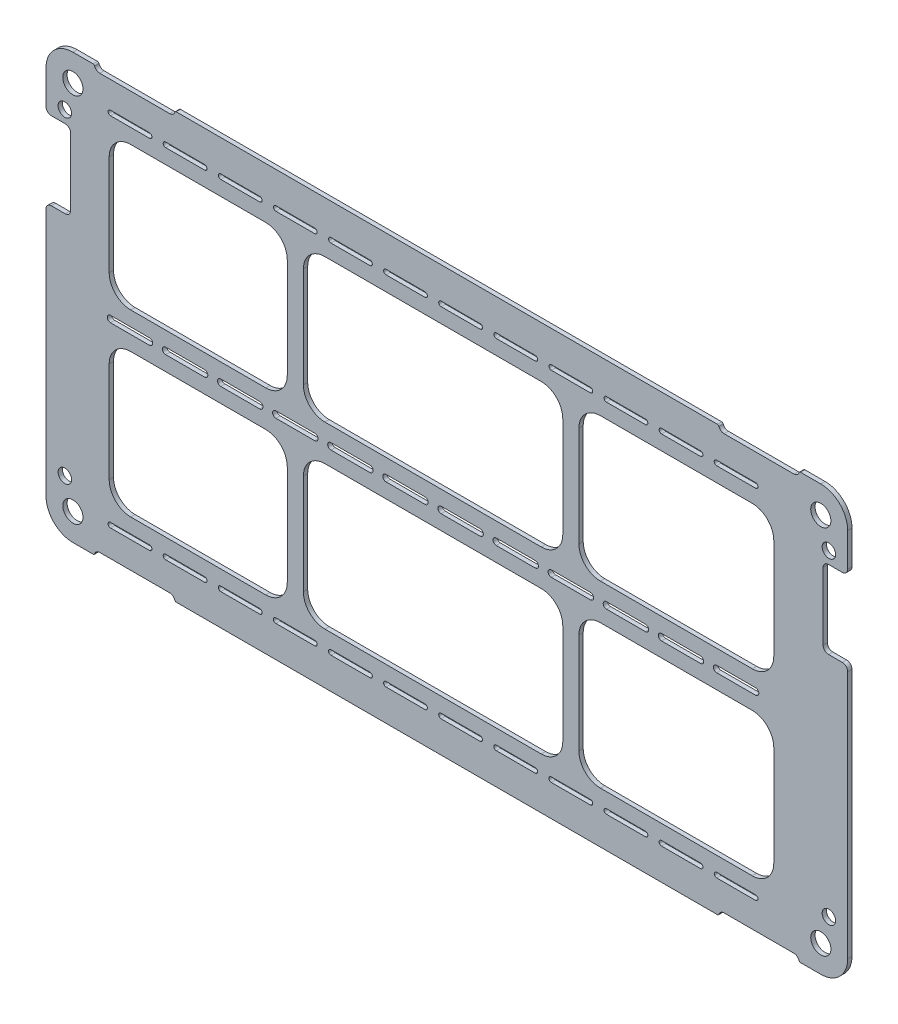
SolidWorks part; units mm, degrees
material "Epoxy, Unfilled"
ref_plane "Front Plane" through (0, 0, 0) normal (0, 0, 1) x (1, 0, 0)
ref_plane "Top Plane" through (0, 0, 0) normal (0, 1, 0) x (1, 0, 0)
ref_plane "Right Plane" through (0, 0, 0) normal (1, 0, 0) x (0, 0, -1)
sketch "Sketch1" plane through (0, 0, 0) normal (0, 0, 1) x (1, 0, 0)
  line L0 (-227.3463, 0) -> (-115.1871, 0) construction
  line L1 (-139.125, -79) -> (-131.5989, -79)
  line L2 (-149.125, -69) -> (-149.125, 23.5)
  line L3 (-139.125, 79) -> (-131.5989, 79)
  line L4 (149.125, -69) -> (149.125, 23.5)
  line L5 (-149.125, -79) -> (149.125, 79) construction
  line L6 (-149.125, 79) -> (149.125, -79) construction
  line L7 (55, 0) -> (-55, 0) construction
  line L8 (0, -65.5957) -> (0, 4.471) construction
  line L9 (0, -55) -> (0, 55) construction
  line L10 (-149.125, 56.5) -> (-149.125, 69)
  line L11 (-147.125, 54.5) -> (-141.975, 54.5)
  line L13 (-147.125, 25.5) -> (-141.975, 25.5)
  line L14 (-139.975, 52.5) -> (-139.975, 27.5)
  line L22 (-59.375, 52) -> (-53.375, 52) construction
  line L23 (-117.625, 60) -> (-67.375, 60)
  line L24 (-125.625, 52) -> (-125.625, 14.7)
  line L25 (-117.625, 6.7) -> (-67.375, 6.7)
  line L26 (-59.375, 52) -> (-59.375, 14.7)
  line L27 (-45.375, 6.7) -> (35.125, 6.7)
  line L28 (-53.375, 14.7) -> (-53.375, 52)
  line L29 (-45.375, 60) -> (35.125, 60)
  line L30 (43.125, 14.7) -> (43.125, 52)
  line L31 (57.125, 60) -> (113.625, 60)
  line L32 (49.125, 52) -> (49.125, 14.7)
  line L33 (57.125, 6.7) -> (113.625, 6.7)
  line L34 (121.625, 52) -> (121.625, 14.7)
  line L35 (43.125, 52) -> (49.125, 52) construction
  line L36 (57.125, -6.7) -> (113.625, -6.7)
  line L37 (121.625, -52) -> (121.625, -14.7)
  line L38 (57.125, -60) -> (113.625, -60)
  line L39 (49.125, -52) -> (49.125, -14.7)
  line L40 (-45.375, -60) -> (35.125, -60)
  line L41 (43.125, -14.7) -> (43.125, -52)
  line L42 (-45.375, -6.7) -> (35.125, -6.7)
  line L43 (-53.375, -14.7) -> (-53.375, -52)
  line L44 (-117.625, -6.7) -> (-67.375, -6.7)
  line L45 (-59.375, -52) -> (-59.375, -14.7)
  line L46 (-117.625, -60) -> (-67.375, -60)
  line L47 (-125.625, -52) -> (-125.625, -14.7)
  line L48 (-125.125, 66.4) -> (-110.625, 66.4) construction
  line L49 (-125.125, 67.3) -> (-110.625, 67.3)
  line L50 (-125.125, 65.5) -> (-110.625, 65.5)
  line L51 (-125.125, 0) -> (-110.625, 0) construction
  line L52 (-125.125, 1.2) -> (-110.625, 1.2)
  line L53 (-125.125, -1.2) -> (-110.625, -1.2)
  line L54 (-117.875, 89.562) -> (-117.875, 51.8241) construction
  line L55 (-125.125, -66.4) -> (-110.625, -66.4) construction
  line L56 (-125.125, -67.3) -> (-110.625, -67.3)
  line L57 (-125.125, -65.5) -> (-110.625, -65.5)
  line L58 (139.975, 52.5) -> (139.975, 27.5)
  line L59 (147.125, 25.5) -> (141.975, 25.5)
  line L60 (147.125, 54.5) -> (141.975, 54.5)
  line L61 (149.125, 56.5) -> (149.125, 69)
  line L62 (-104.625, 66.4) -> (-90.125, 66.4) construction
  line L63 (-104.625, 67.3) -> (-90.125, 67.3)
  line L64 (-104.625, 65.5) -> (-90.125, 65.5)
  line L65 (-104.625, 0) -> (-90.125, 0) construction
  line L66 (-104.625, 1.2) -> (-90.125, 1.2)
  line L67 (-104.625, -1.2) -> (-90.125, -1.2)
  line L68 (-104.625, -66.4) -> (-90.125, -66.4) construction
  line L69 (-104.625, -67.3) -> (-90.125, -67.3)
  line L70 (-104.625, -65.5) -> (-90.125, -65.5)
  line L71 (-84.125, 66.4) -> (-69.625, 66.4) construction
  line L72 (-84.125, 67.3) -> (-69.625, 67.3)
  line L73 (-84.125, 65.5) -> (-69.625, 65.5)
  line L74 (-84.125, 0) -> (-69.625, 0) construction
  line L75 (-84.125, 1.2) -> (-69.625, 1.2)
  line L76 (-84.125, -1.2) -> (-69.625, -1.2)
  line L77 (-84.125, -66.4) -> (-69.625, -66.4) construction
  line L78 (-84.125, -67.3) -> (-69.625, -67.3)
  line L79 (-84.125, -65.5) -> (-69.625, -65.5)
  line L80 (-63.625, 66.4) -> (-49.125, 66.4) construction
  line L81 (-63.625, 67.3) -> (-49.125, 67.3)
  line L82 (-63.625, 65.5) -> (-49.125, 65.5)
  line L83 (-63.625, 0) -> (-49.125, 0) construction
  line L84 (-63.625, 1.2) -> (-49.125, 1.2)
  line L85 (-63.625, -1.2) -> (-49.125, -1.2)
  line L86 (-63.625, -66.4) -> (-49.125, -66.4) construction
  line L87 (-63.625, -67.3) -> (-49.125, -67.3)
  line L88 (-63.625, -65.5) -> (-49.125, -65.5)
  line L89 (-43.125, 66.4) -> (-28.625, 66.4) construction
  line L90 (-43.125, 67.3) -> (-28.625, 67.3)
  line L91 (-43.125, 65.5) -> (-28.625, 65.5)
  line L92 (-43.125, 0) -> (-28.625, 0) construction
  line L93 (-43.125, 1.2) -> (-28.625, 1.2)
  line L94 (-43.125, -1.2) -> (-28.625, -1.2)
  line L95 (-43.125, -66.4) -> (-28.625, -66.4) construction
  line L96 (-43.125, -67.3) -> (-28.625, -67.3)
  line L97 (-43.125, -65.5) -> (-28.625, -65.5)
  line L98 (-22.625, 66.4) -> (-8.125, 66.4) construction
  line L99 (-22.625, 67.3) -> (-8.125, 67.3)
  line L100 (-22.625, 65.5) -> (-8.125, 65.5)
  line L101 (-22.625, 0) -> (-8.125, 0) construction
  line L102 (-22.625, 1.2) -> (-8.125, 1.2)
  line L103 (-22.625, -1.2) -> (-8.125, -1.2)
  line L104 (-22.625, -66.4) -> (-8.125, -66.4) construction
  line L105 (-22.625, -67.3) -> (-8.125, -67.3)
  line L106 (-22.625, -65.5) -> (-8.125, -65.5)
  line L107 (-2.125, 66.4) -> (12.375, 66.4) construction
  line L108 (-2.125, 67.3) -> (12.375, 67.3)
  line L109 (-2.125, 65.5) -> (12.375, 65.5)
  line L110 (-2.125, 0) -> (12.375, 0) construction
  line L111 (-2.125, 1.2) -> (12.375, 1.2)
  line L112 (-2.125, -1.2) -> (12.375, -1.2)
  line L113 (-2.125, -66.4) -> (12.375, -66.4) construction
  line L114 (-2.125, -67.3) -> (12.375, -67.3)
  line L115 (-2.125, -65.5) -> (12.375, -65.5)
  line L116 (18.375, 66.4) -> (32.875, 66.4) construction
  line L117 (18.375, 67.3) -> (32.875, 67.3)
  line L118 (18.375, 65.5) -> (32.875, 65.5)
  line L119 (18.375, 0) -> (32.875, 0) construction
  line L120 (18.375, 1.2) -> (32.875, 1.2)
  line L121 (18.375, -1.2) -> (32.875, -1.2)
  line L122 (18.375, -66.4) -> (32.875, -66.4) construction
  line L123 (18.375, -67.3) -> (32.875, -67.3)
  line L124 (18.375, -65.5) -> (32.875, -65.5)
  line L125 (38.875, 66.4) -> (53.375, 66.4) construction
  line L126 (38.875, 67.3) -> (53.375, 67.3)
  line L127 (38.875, 65.5) -> (53.375, 65.5)
  line L128 (38.875, 0) -> (53.375, 0) construction
  line L129 (38.875, 1.2) -> (53.375, 1.2)
  line L130 (38.875, -1.2) -> (53.375, -1.2)
  line L131 (38.875, -66.4) -> (53.375, -66.4) construction
  line L132 (38.875, -67.3) -> (53.375, -67.3)
  line L133 (38.875, -65.5) -> (53.375, -65.5)
  line L134 (59.375, 66.4) -> (73.875, 66.4) construction
  line L135 (59.375, 67.3) -> (73.875, 67.3)
  line L136 (59.375, 65.5) -> (73.875, 65.5)
  line L137 (59.375, 0) -> (73.875, 0) construction
  line L138 (59.375, 1.2) -> (73.875, 1.2)
  line L139 (59.375, -1.2) -> (73.875, -1.2)
  line L140 (59.375, -66.4) -> (73.875, -66.4) construction
  line L141 (59.375, -67.3) -> (73.875, -67.3)
  line L142 (59.375, -65.5) -> (73.875, -65.5)
  line L143 (79.875, 66.4) -> (94.375, 66.4) construction
  line L144 (79.875, 67.3) -> (94.375, 67.3)
  line L145 (79.875, 65.5) -> (94.375, 65.5)
  line L146 (79.875, 0) -> (94.375, 0) construction
  line L147 (79.875, 1.2) -> (94.375, 1.2)
  line L148 (79.875, -1.2) -> (94.375, -1.2)
  line L149 (79.875, -66.4) -> (94.375, -66.4) construction
  line L150 (79.875, -67.3) -> (94.375, -67.3)
  line L151 (79.875, -65.5) -> (94.375, -65.5)
  line L152 (100.375, 66.4) -> (114.875, 66.4) construction
  line L153 (100.375, 67.3) -> (114.875, 67.3)
  line L154 (100.375, 65.5) -> (114.875, 65.5)
  line L155 (100.375, 0) -> (114.875, 0) construction
  line L156 (100.375, 1.2) -> (114.875, 1.2)
  line L157 (100.375, -1.2) -> (114.875, -1.2)
  line L158 (100.375, -66.4) -> (114.875, -66.4) construction
  line L159 (100.375, -67.3) -> (114.875, -67.3)
  line L160 (100.375, -65.5) -> (114.875, -65.5)
  line L161 (-56.375, 54.9) -> (-56.375, 60.9) construction
  line L162 (46.125, 113.9589) -> (46.125, 95.0185) construction
  line L163 (107.625, 88.9765) -> (107.625, 49.3682) construction
  line L167 (-129.125, 77.2) -> (-103.125, 77.2)
  line L169 (-100.6511, 79) -> (100.6511, 79)
  line L173 (131.5989, 79) -> (139.125, 79)
  line L180 (-100.6511, -79) -> (100.6511, -79)
  line L181 (131.5989, -79) -> (139.125, -79)
  line L182 (129.125, 77.2) -> (103.125, 77.2)
  line L183 (-129.125, -77.2) -> (-103.125, -77.2)
  line L184 (129.125, -77.2) -> (103.125, -77.2)
  line L185 (-117.875, 0) -> (107.625, 0) construction
  line L186 (-5.125, 0) -> (-5.125, -15.4812) construction
  arc A0 (139.125, 79) -> (149.125, 69) centre (139.125, 69) cw
  arc A1 (-149.125, 69) -> (-139.125, 79) centre (-139.125, 69) cw
  arc A2 (-139.125, -79) -> (-149.125, -69) centre (-139.125, -69) cw
  arc A3 (139.125, -79) -> (149.125, -69) centre (139.125, -69) ccw
  arc A4 (-147.125, 54.5) -> (-149.125, 56.5) centre (-147.125, 56.5) cw
  arc A5 (-141.975, 54.5) -> (-139.975, 52.5) centre (-141.975, 52.5) cw
  arc A6 (-141.975, 25.5) -> (-139.975, 27.5) centre (-141.975, 27.5) ccw
  arc A7 (-149.125, 23.5) -> (-147.125, 25.5) centre (-147.125, 23.5) cw
  arc A16 (113.625, 60) -> (121.625, 52) centre (113.625, 52) cw
  arc A17 (113.625, 6.7) -> (121.625, 14.7) centre (113.625, 14.7) ccw
  arc A18 (49.125, 14.7) -> (57.125, 6.7) centre (57.125, 14.7) ccw
  arc A19 (57.125, 60) -> (49.125, 52) centre (57.125, 52) ccw
  arc A20 (35.125, 60) -> (43.125, 52) centre (35.125, 52) cw
  arc A21 (35.125, 6.7) -> (43.125, 14.7) centre (35.125, 14.7) ccw
  arc A22 (-45.375, 6.7) -> (-53.375, 14.7) centre (-45.375, 14.7) cw
  arc A23 (-53.375, 52) -> (-45.375, 60) centre (-45.375, 52) cw
  arc A24 (-67.375, 60) -> (-59.375, 52) centre (-67.375, 52) cw
  arc A25 (-67.375, 6.7) -> (-59.375, 14.7) centre (-67.375, 14.7) ccw
  arc A26 (-125.625, 14.7) -> (-117.625, 6.7) centre (-117.625, 14.7) ccw
  arc A27 (-125.625, 52) -> (-117.625, 60) centre (-117.625, 52) cw
  arc A28 (113.625, -6.7) -> (121.625, -14.7) centre (113.625, -14.7) cw
  arc A29 (113.625, -60) -> (121.625, -52) centre (113.625, -52) ccw
  arc A30 (49.125, -14.7) -> (57.125, -6.7) centre (57.125, -14.7) cw
  arc A31 (57.125, -60) -> (49.125, -52) centre (57.125, -52) cw
  arc A32 (35.125, -60) -> (43.125, -52) centre (35.125, -52) ccw
  arc A33 (35.125, -6.7) -> (43.125, -14.7) centre (35.125, -14.7) cw
  arc A34 (-45.375, -6.7) -> (-53.375, -14.7) centre (-45.375, -14.7) ccw
  arc A35 (-53.375, -52) -> (-45.375, -60) centre (-45.375, -52) ccw
  arc A36 (-67.375, -6.7) -> (-59.375, -14.7) centre (-67.375, -14.7) cw
  arc A37 (-67.375, -60) -> (-59.375, -52) centre (-67.375, -52) ccw
  arc A38 (-125.625, -14.7) -> (-117.625, -6.7) centre (-117.625, -14.7) cw
  arc A39 (-125.625, -52) -> (-117.625, -60) centre (-117.625, -52) ccw
  arc A40 (-125.125, 67.3) -> (-125.125, 65.5) centre (-125.125, 66.4) ccw
  arc A41 (-110.625, 65.5) -> (-110.625, 67.3) centre (-110.625, 66.4) ccw
  arc A42 (-125.125, 1.2) -> (-125.125, -1.2) centre (-125.125, 0) ccw
  arc A43 (-110.625, -1.2) -> (-110.625, 1.2) centre (-110.625, 0) ccw
  arc A44 (-125.125, -67.3) -> (-125.125, -65.5) centre (-125.125, -66.4) cw
  arc A45 (-110.625, -65.5) -> (-110.625, -67.3) centre (-110.625, -66.4) cw
  circle A46 centre (-139.125, 69) radius 3.75
  circle A47 centre (-139.125, -69) radius 3.75
  circle A48 centre (139.125, -69) radius 3.75
  circle A49 centre (139.125, 69) radius 3.75
  arc A50 (149.125, 23.5) -> (147.125, 25.5) centre (147.125, 23.5) ccw
  arc A51 (141.975, 25.5) -> (139.975, 27.5) centre (141.975, 27.5) cw
  arc A52 (141.975, 54.5) -> (139.975, 52.5) centre (141.975, 52.5) ccw
  arc A53 (147.125, 54.5) -> (149.125, 56.5) centre (147.125, 56.5) ccw
  arc A54 (-104.625, 67.3) -> (-104.625, 65.5) centre (-104.625, 66.4) ccw
  arc A55 (-90.125, 65.5) -> (-90.125, 67.3) centre (-90.125, 66.4) ccw
  arc A56 (-104.625, 1.2) -> (-104.625, -1.2) centre (-104.625, 0) ccw
  arc A57 (-90.125, -1.2) -> (-90.125, 1.2) centre (-90.125, 0) ccw
  arc A58 (-104.625, -67.3) -> (-104.625, -65.5) centre (-104.625, -66.4) cw
  arc A59 (-90.125, -65.5) -> (-90.125, -67.3) centre (-90.125, -66.4) cw
  arc A60 (-84.125, 67.3) -> (-84.125, 65.5) centre (-84.125, 66.4) ccw
  arc A61 (-69.625, 65.5) -> (-69.625, 67.3) centre (-69.625, 66.4) ccw
  arc A62 (-84.125, 1.2) -> (-84.125, -1.2) centre (-84.125, 0) ccw
  arc A63 (-69.625, -1.2) -> (-69.625, 1.2) centre (-69.625, 0) ccw
  arc A64 (-84.125, -67.3) -> (-84.125, -65.5) centre (-84.125, -66.4) cw
  arc A65 (-69.625, -65.5) -> (-69.625, -67.3) centre (-69.625, -66.4) cw
  arc A66 (-63.625, 67.3) -> (-63.625, 65.5) centre (-63.625, 66.4) ccw
  arc A67 (-49.125, 65.5) -> (-49.125, 67.3) centre (-49.125, 66.4) ccw
  arc A68 (-63.625, 1.2) -> (-63.625, -1.2) centre (-63.625, 0) ccw
  arc A69 (-49.125, -1.2) -> (-49.125, 1.2) centre (-49.125, 0) ccw
  arc A70 (-63.625, -67.3) -> (-63.625, -65.5) centre (-63.625, -66.4) cw
  arc A71 (-49.125, -65.5) -> (-49.125, -67.3) centre (-49.125, -66.4) cw
  arc A72 (-43.125, 67.3) -> (-43.125, 65.5) centre (-43.125, 66.4) ccw
  arc A73 (-28.625, 65.5) -> (-28.625, 67.3) centre (-28.625, 66.4) ccw
  arc A74 (-43.125, 1.2) -> (-43.125, -1.2) centre (-43.125, 0) ccw
  arc A75 (-28.625, -1.2) -> (-28.625, 1.2) centre (-28.625, 0) ccw
  arc A76 (-43.125, -67.3) -> (-43.125, -65.5) centre (-43.125, -66.4) cw
  arc A77 (-28.625, -65.5) -> (-28.625, -67.3) centre (-28.625, -66.4) cw
  arc A78 (-22.625, 67.3) -> (-22.625, 65.5) centre (-22.625, 66.4) ccw
  arc A79 (-8.125, 65.5) -> (-8.125, 67.3) centre (-8.125, 66.4) ccw
  arc A80 (-22.625, 1.2) -> (-22.625, -1.2) centre (-22.625, 0) ccw
  arc A81 (-8.125, -1.2) -> (-8.125, 1.2) centre (-8.125, 0) ccw
  arc A82 (-22.625, -67.3) -> (-22.625, -65.5) centre (-22.625, -66.4) cw
  arc A83 (-8.125, -65.5) -> (-8.125, -67.3) centre (-8.125, -66.4) cw
  arc A84 (-2.125, 67.3) -> (-2.125, 65.5) centre (-2.125, 66.4) ccw
  arc A85 (12.375, 65.5) -> (12.375, 67.3) centre (12.375, 66.4) ccw
  arc A86 (-2.125, 1.2) -> (-2.125, -1.2) centre (-2.125, 0) ccw
  arc A87 (12.375, -1.2) -> (12.375, 1.2) centre (12.375, 0) ccw
  arc A88 (-2.125, -67.3) -> (-2.125, -65.5) centre (-2.125, -66.4) cw
  arc A89 (12.375, -65.5) -> (12.375, -67.3) centre (12.375, -66.4) cw
  arc A90 (18.375, 67.3) -> (18.375, 65.5) centre (18.375, 66.4) ccw
  arc A91 (32.875, 65.5) -> (32.875, 67.3) centre (32.875, 66.4) ccw
  arc A92 (18.375, 1.2) -> (18.375, -1.2) centre (18.375, 0) ccw
  arc A93 (32.875, -1.2) -> (32.875, 1.2) centre (32.875, 0) ccw
  arc A94 (18.375, -67.3) -> (18.375, -65.5) centre (18.375, -66.4) cw
  arc A95 (32.875, -65.5) -> (32.875, -67.3) centre (32.875, -66.4) cw
  arc A96 (38.875, 67.3) -> (38.875, 65.5) centre (38.875, 66.4) ccw
  arc A97 (53.375, 65.5) -> (53.375, 67.3) centre (53.375, 66.4) ccw
  arc A98 (38.875, 1.2) -> (38.875, -1.2) centre (38.875, 0) ccw
  arc A99 (53.375, -1.2) -> (53.375, 1.2) centre (53.375, 0) ccw
  arc A100 (38.875, -67.3) -> (38.875, -65.5) centre (38.875, -66.4) cw
  arc A101 (53.375, -65.5) -> (53.375, -67.3) centre (53.375, -66.4) cw
  arc A102 (59.375, 67.3) -> (59.375, 65.5) centre (59.375, 66.4) ccw
  arc A103 (73.875, 65.5) -> (73.875, 67.3) centre (73.875, 66.4) ccw
  arc A104 (59.375, 1.2) -> (59.375, -1.2) centre (59.375, 0) ccw
  arc A105 (73.875, -1.2) -> (73.875, 1.2) centre (73.875, 0) ccw
  arc A106 (59.375, -67.3) -> (59.375, -65.5) centre (59.375, -66.4) cw
  arc A107 (73.875, -65.5) -> (73.875, -67.3) centre (73.875, -66.4) cw
  arc A108 (79.875, 67.3) -> (79.875, 65.5) centre (79.875, 66.4) ccw
  arc A109 (94.375, 65.5) -> (94.375, 67.3) centre (94.375, 66.4) ccw
  arc A110 (79.875, 1.2) -> (79.875, -1.2) centre (79.875, 0) ccw
  arc A111 (94.375, -1.2) -> (94.375, 1.2) centre (94.375, 0) ccw
  arc A112 (79.875, -67.3) -> (79.875, -65.5) centre (79.875, -66.4) cw
  arc A113 (94.375, -65.5) -> (94.375, -67.3) centre (94.375, -66.4) cw
  arc A114 (100.375, 67.3) -> (100.375, 65.5) centre (100.375, 66.4) ccw
  arc A115 (114.875, 65.5) -> (114.875, 67.3) centre (114.875, 66.4) ccw
  arc A116 (100.375, 1.2) -> (100.375, -1.2) centre (100.375, 0) ccw
  arc A117 (114.875, -1.2) -> (114.875, 1.2) centre (114.875, 0) ccw
  arc A118 (100.375, -67.3) -> (100.375, -65.5) centre (100.375, -66.4) cw
  arc A119 (114.875, -65.5) -> (114.875, -67.3) centre (114.875, -66.4) cw
  arc A120 (-100.6511, 79) -> (-101.222, 78.5846) centre (-100.6511, 78.4) ccw
  arc A121 (-103.125, 77.2) -> (-101.222, 78.5846) centre (-103.125, 79.2) ccw
  arc A122 (-131.028, 78.5846) -> (-129.125, 77.2) centre (-129.125, 79.2) ccw
  arc A123 (-131.5989, 79) -> (-131.028, 78.5846) centre (-131.5989, 78.4) cw
  arc A124 (131.5989, 79) -> (131.028, 78.5846) centre (131.5989, 78.4) ccw
  arc A125 (131.028, 78.5846) -> (129.125, 77.2) centre (129.125, 79.2) cw
  arc A126 (103.125, 77.2) -> (101.222, 78.5846) centre (103.125, 79.2) cw
  arc A127 (100.6511, 79) -> (101.222, 78.5846) centre (100.6511, 78.4) cw
  arc A128 (-131.5989, -79) -> (-131.028, -78.5846) centre (-131.5989, -78.4) ccw
  arc A129 (-131.028, -78.5846) -> (-129.125, -77.2) centre (-129.125, -79.2) cw
  arc A130 (-103.125, -77.2) -> (-101.222, -78.5846) centre (-103.125, -79.2) cw
  arc A131 (-100.6511, -79) -> (-101.222, -78.5846) centre (-100.6511, -78.4) cw
  arc A132 (100.6511, -79) -> (101.222, -78.5846) centre (100.6511, -78.4) ccw
  arc A133 (103.125, -77.2) -> (101.222, -78.5846) centre (103.125, -79.2) ccw
  arc A134 (131.028, -78.5846) -> (129.125, -77.2) centre (129.125, -79.2) ccw
  arc A135 (131.5989, -79) -> (131.028, -78.5846) centre (131.5989, -78.4) cw
  circle A136 centre (-142.125, 59) radius 2.5
  circle A137 centre (142.125, 59) radius 2.5
  circle A138 centre (142.125, -59) radius 2.5
  circle A139 centre (-142.125, -59) radius 2.5
  point P0 (0, 0)
  point P31 (-149.125, 54.5)
  point P124 (-117.875, 66.4)
  point P133 (-117.875, 0)
  point P142 (149.125, 54.5)
  point P146 (-117.875, -66.4)
  point P154 (-97.375, 66.4)
  point P161 (-97.375, 0)
  point P168 (-97.375, -66.4)
  point P175 (-76.875, 66.4)
  point P182 (-76.875, 0)
  point P189 (-76.875, -66.4)
  point P196 (-56.375, 66.4)
  point P203 (-56.375, 0)
  point P210 (-56.375, -66.4)
  point P217 (-35.875, 66.4)
  point P224 (-35.875, 0)
  point P231 (-35.875, -66.4)
  point P238 (-15.375, 66.4)
  point P245 (-15.375, 0)
  point P252 (-15.375, -66.4)
  point P259 (5.125, 66.4)
  point P266 (5.125, 0)
  point P273 (5.125, -66.4)
  point P280 (25.625, 66.4)
  point P287 (25.625, 0)
  point P294 (25.625, -66.4)
  point P301 (46.125, 66.4)
  point P308 (46.125, 0)
  point P315 (46.125, -66.4)
  point P322 (66.625, 66.4)
  point P329 (66.625, 0)
  point P336 (66.625, -66.4)
  point P343 (87.125, 66.4)
  point P350 (87.125, 0)
  point P357 (87.125, -66.4)
  point P364 (107.625, 66.4)
  point P371 (107.625, 0)
  point P378 (107.625, -66.4)
  point P383 (-56.375, 52)
  point P384 (-56.375, 52)
  point P385 (-56.375, 52)
  point P386 (-56.375, 52)
  point P387 (46.125, 52)
  point P405 (-5.125, 0)
  dimension "D3" = 10
  dimension "D4" = 2
  dimension "D8" = 8
  dimension "D22" = 7.5
  dimension "D33" = 0.6
  dimension "D37" = 2
  dimension "D35" = 5
  dimension "D1" = 298.25
  dimension "D2" = 158
  dimension "D5" = 24.5
  dimension "D6" = 29
  dimension "D7" = 9.15
  dimension "D9" = 6
  dimension "D10" = 247.25
  dimension "D11" = 14.35
  dimension "D12" = 23.5
  dimension "D15" = 13.4
  dimension "D16" = 53.3
  dimension "D17" = 1.8
  dimension "D18" = 14.5
  dimension "D19" = 7.75
  dimension "D21" = 2.4
  dimension "D24" = 19
  dimension "D23" = 5.5
  dimension "D14" = 5.5
  dimension "D25" = 20.5
  dimension "D28" = 18.35
  dimension "D29" = 6.25
  dimension "D30" = 285.75
  dimension "D26" = 14
  dimension "D27" = 21.25
  dimension "D31" = 31.5
  dimension "D36" = 26
  dimension "D34" = 1.8
  dimension "D32" = 20
  dimension "D38" = 7
  dimension "D39" = 20
  dimension "D40" = 16.3
  dimension "D41" = 225.5
  dimension "D42" = 23.5
  dimension "D43" = 27.5
  dimension "D44" = 66.4
  dimension "D20" = 66.4
  dimension "D45" = 64.3
  dimension "D13" = 12
extrude "Boss-Extrude1" add sketch "Sketch1" along normal blind 1.6
ref_plane "Bank Divider Plane" through (0, 0, 0) normal (0, -1, 0) x (1, 0, 0)
ref_plane "Near Cell Divider Plane" through (-117.875, 0, 0) normal (-1, 0, 0) x (0, -1, 0)
ref_plane "Near Rib Divider Plane" through (-56.375, 0, 0) normal (1, 0, 0) x (0, 1, 0)
ref_plane "Slot Pattern Midplane" through (-5.125, 0, 0) normal (-1, 0, 0) x (0, -1, 0)
sketch "Sketch2" plane through (0, 0, 1.6) normal (0, 0, 1) x (1, 0, 0)
  line L0 (-80.05, 60) -> (-73.7, 60)
  line L1 (-80.05, 64) -> (-80.05, 60)
  line L2 (-73.7, 64) -> (-80.05, 64)
  line L3 (-73.7, 64) -> (-73.7, 60)
  line L4 (-73.7, 2.7) -> (-73.7, 6.7)
  line L5 (-73.7, 2.7) -> (-80.05, 2.7)
  line L6 (-80.05, 2.7) -> (-80.05, 6.7)
  line L7 (-80.05, 6.7) -> (-73.7, 6.7)
  line L9 (-121.05, 60) -> (-114.7, 60)
  line L10 (-121.05, 64) -> (-121.05, 60)
  line L11 (-114.7, 64) -> (-121.05, 64)
  line L12 (-80.05, -6.7) -> (-73.7, -6.7)
  line L13 (-80.05, -2.7) -> (-80.05, -6.7)
  line L14 (-73.7, -2.7) -> (-80.05, -2.7)
  line L15 (-73.7, -2.7) -> (-73.7, -6.7)
  line L20 (-114.7, 64) -> (-114.7, 60)
  line L21 (-114.7, 2.7) -> (-114.7, 6.7)
  line L22 (-114.7, 2.7) -> (-121.05, 2.7)
  line L23 (-121.05, 2.7) -> (-121.05, 6.7)
  line L24 (-121.05, 6.7) -> (-114.7, 6.7)
  line L25 (-208.7222, 0) -> (-236.5604, 0) construction
  line L26 (55, 0) -> (-55, 0) construction
  line L27 (-121.05, -6.7) -> (-114.7, -6.7)
  line L28 (-121.05, -2.7) -> (-121.05, -6.7)
  line L29 (-114.7, -2.7) -> (-121.05, -2.7)
  line L30 (-114.7, -2.7) -> (-114.7, -6.7)
  line L31 (-114.7, -64) -> (-114.7, -60)
  line L32 (-114.7, -64) -> (-121.05, -64)
  line L33 (-121.05, -64) -> (-121.05, -60)
  line L34 (-121.05, -60) -> (-114.7, -60)
  line L35 (-100.55, 60) -> (-94.2, 60)
  line L36 (-100.55, 64) -> (-100.55, 60)
  line L37 (-94.2, 64) -> (-100.55, 64)
  line L38 (-94.2, 64) -> (-94.2, 60)
  line L39 (-94.2, 2.7) -> (-94.2, 6.7)
  line L68 (-117.875, 156.7264) -> (-117.875, 42.2557) construction
  line L69 (-117.875, 23.9358) -> (-117.875, -23.9358) construction
  line L70 (-92.5, 60) -> (-92.5, 6.7) construction
  line L71 (-67.375, 60) -> (-117.625, 60) construction
  line L72 (-117.625, 6.7) -> (-67.375, 6.7) construction
  line L73 (-92.5, 33.35) -> (-117.875, 33.35) construction
  line L74 (-94.2, 2.7) -> (-100.55, 2.7)
  line L75 (-100.55, 2.7) -> (-100.55, 6.7)
  line L76 (-100.55, 6.7) -> (-94.2, 6.7)
  line L77 (-100.55, -6.7) -> (-94.2, -6.7)
  line L78 (-100.55, -2.7) -> (-100.55, -6.7)
  line L79 (-94.2, -2.7) -> (-100.55, -2.7)
  line L80 (-94.2, -2.7) -> (-94.2, -6.7)
  line L81 (-94.2, -64) -> (-94.2, -60)
  line L82 (-94.2, -64) -> (-100.55, -64)
  line L83 (-100.55, -64) -> (-100.55, -60)
  line L84 (-100.55, -60) -> (-94.2, -60)
  line L85 (-121.05, 60) -> (-100.55, 60) construction
  line L86 (-73.7, -64) -> (-73.7, -60)
  line L87 (-73.7, -64) -> (-80.05, -64)
  line L88 (-80.05, -64) -> (-80.05, -60)
  line L89 (-80.05, -60) -> (-73.7, -60)
  line L90 (-59.55, 60) -> (-53.2, 60)
  line L91 (-59.55, 64) -> (-59.55, 60)
  line L92 (-53.2, 64) -> (-59.55, 64)
  line L93 (-53.2, 64) -> (-53.2, 60)
  line L94 (-53.2, 2.7) -> (-53.2, 6.7)
  line L95 (-53.2, 2.7) -> (-59.55, 2.7)
  line L96 (-59.55, 2.7) -> (-59.55, 6.7)
  line L97 (-59.55, 6.7) -> (-53.2, 6.7)
  line L98 (-59.55, -6.7) -> (-53.2, -6.7)
  line L99 (-59.55, -2.7) -> (-59.55, -6.7)
  line L100 (-53.2, -2.7) -> (-59.55, -2.7)
  line L101 (-53.2, -2.7) -> (-53.2, -6.7)
  line L102 (-53.2, -64) -> (-53.2, -60)
  line L103 (-53.2, -64) -> (-59.55, -64)
  line L104 (-59.55, -64) -> (-59.55, -60)
  line L105 (-59.55, -60) -> (-53.2, -60)
  line L106 (-39.05, 60) -> (-32.7, 60)
  line L107 (-39.05, 64) -> (-39.05, 60)
  line L108 (-32.7, 64) -> (-39.05, 64)
  line L109 (-32.7, 64) -> (-32.7, 60)
  line L110 (-32.7, 2.7) -> (-32.7, 6.7)
  line L111 (-32.7, 2.7) -> (-39.05, 2.7)
  line L112 (-39.05, 2.7) -> (-39.05, 6.7)
  line L113 (-39.05, 6.7) -> (-32.7, 6.7)
  line L114 (-39.05, -6.7) -> (-32.7, -6.7)
  line L115 (-39.05, -2.7) -> (-39.05, -6.7)
  line L116 (-32.7, -2.7) -> (-39.05, -2.7)
  line L117 (-32.7, -2.7) -> (-32.7, -6.7)
  line L118 (-32.7, -64) -> (-32.7, -60)
  line L119 (-32.7, -64) -> (-39.05, -64)
  line L120 (-39.05, -64) -> (-39.05, -60)
  line L121 (-39.05, -60) -> (-32.7, -60)
  line L122 (-18.55, 60) -> (-12.2, 60)
  line L123 (-18.55, 64) -> (-18.55, 60)
  line L124 (-12.2, 64) -> (-18.55, 64)
  line L125 (-12.2, 64) -> (-12.2, 60)
  line L126 (-12.2, 2.7) -> (-12.2, 6.7)
  line L127 (-12.2, 2.7) -> (-18.55, 2.7)
  line L128 (-18.55, 2.7) -> (-18.55, 6.7)
  line L129 (-18.55, 6.7) -> (-12.2, 6.7)
  line L130 (-18.55, -6.7) -> (-12.2, -6.7)
  line L131 (-18.55, -2.7) -> (-18.55, -6.7)
  line L132 (-12.2, -2.7) -> (-18.55, -2.7)
  line L133 (-12.2, -2.7) -> (-12.2, -6.7)
  line L134 (-12.2, -64) -> (-12.2, -60)
  line L135 (-12.2, -64) -> (-18.55, -64)
  line L136 (-18.55, -64) -> (-18.55, -60)
  line L137 (-18.55, -60) -> (-12.2, -60)
  line L138 (1.95, 60) -> (8.3, 60)
  line L139 (1.95, 64) -> (1.95, 60)
  line L140 (8.3, 64) -> (1.95, 64)
  line L141 (8.3, 64) -> (8.3, 60)
  line L142 (8.3, 2.7) -> (8.3, 6.7)
  line L143 (8.3, 2.7) -> (1.95, 2.7)
  line L144 (1.95, 2.7) -> (1.95, 6.7)
  line L145 (1.95, 6.7) -> (8.3, 6.7)
  line L146 (1.95, -6.7) -> (8.3, -6.7)
  line L147 (1.95, -2.7) -> (1.95, -6.7)
  line L148 (8.3, -2.7) -> (1.95, -2.7)
  line L149 (8.3, -2.7) -> (8.3, -6.7)
  line L150 (8.3, -64) -> (8.3, -60)
  line L151 (8.3, -64) -> (1.95, -64)
  line L152 (1.95, -64) -> (1.95, -60)
  line L153 (1.95, -60) -> (8.3, -60)
  line L154 (22.45, 60) -> (28.8, 60)
  line L155 (22.45, 64) -> (22.45, 60)
  line L156 (28.8, 64) -> (22.45, 64)
  line L157 (28.8, 64) -> (28.8, 60)
  line L158 (28.8, 2.7) -> (28.8, 6.7)
  line L159 (28.8, 2.7) -> (22.45, 2.7)
  line L160 (22.45, 2.7) -> (22.45, 6.7)
  line L161 (22.45, 6.7) -> (28.8, 6.7)
  line L162 (22.45, -6.7) -> (28.8, -6.7)
  line L163 (22.45, -2.7) -> (22.45, -6.7)
  line L164 (28.8, -2.7) -> (22.45, -2.7)
  line L165 (28.8, -2.7) -> (28.8, -6.7)
  line L166 (28.8, -64) -> (28.8, -60)
  line L167 (28.8, -64) -> (22.45, -64)
  line L168 (22.45, -64) -> (22.45, -60)
  line L169 (22.45, -60) -> (28.8, -60)
  line L170 (42.95, 60) -> (49.3, 60)
  line L171 (42.95, 64) -> (42.95, 60)
  line L172 (49.3, 64) -> (42.95, 64)
  line L173 (49.3, 64) -> (49.3, 60)
  line L174 (49.3, 2.7) -> (49.3, 6.7)
  line L175 (49.3, 2.7) -> (42.95, 2.7)
  line L176 (42.95, 2.7) -> (42.95, 6.7)
  line L177 (42.95, 6.7) -> (49.3, 6.7)
  line L178 (42.95, -6.7) -> (49.3, -6.7)
  line L179 (42.95, -2.7) -> (42.95, -6.7)
  line L180 (49.3, -2.7) -> (42.95, -2.7)
  line L181 (49.3, -2.7) -> (49.3, -6.7)
  line L182 (49.3, -64) -> (49.3, -60)
  line L183 (49.3, -64) -> (42.95, -64)
  line L184 (42.95, -64) -> (42.95, -60)
  line L185 (42.95, -60) -> (49.3, -60)
  line L186 (63.45, 60) -> (69.8, 60)
  line L187 (63.45, 64) -> (63.45, 60)
  line L188 (69.8, 64) -> (63.45, 64)
  line L189 (69.8, 64) -> (69.8, 60)
  line L190 (69.8, 2.7) -> (69.8, 6.7)
  line L191 (69.8, 2.7) -> (63.45, 2.7)
  line L192 (63.45, 2.7) -> (63.45, 6.7)
  line L193 (63.45, 6.7) -> (69.8, 6.7)
  line L194 (63.45, -6.7) -> (69.8, -6.7)
  line L195 (63.45, -2.7) -> (63.45, -6.7)
  line L196 (69.8, -2.7) -> (63.45, -2.7)
  line L197 (69.8, -2.7) -> (69.8, -6.7)
  line L198 (69.8, -64) -> (69.8, -60)
  line L199 (69.8, -64) -> (63.45, -64)
  line L200 (63.45, -64) -> (63.45, -60)
  line L201 (63.45, -60) -> (69.8, -60)
  line L202 (83.95, 60) -> (90.3, 60)
  line L203 (83.95, 64) -> (83.95, 60)
  line L204 (90.3, 64) -> (83.95, 64)
  line L205 (90.3, 64) -> (90.3, 60)
  line L206 (90.3, 2.7) -> (90.3, 6.7)
  line L207 (90.3, 2.7) -> (83.95, 2.7)
  line L208 (83.95, 2.7) -> (83.95, 6.7)
  line L209 (83.95, 6.7) -> (90.3, 6.7)
  line L210 (83.95, -6.7) -> (90.3, -6.7)
  line L211 (83.95, -2.7) -> (83.95, -6.7)
  line L212 (90.3, -2.7) -> (83.95, -2.7)
  line L213 (90.3, -2.7) -> (90.3, -6.7)
  line L214 (90.3, -64) -> (90.3, -60)
  line L215 (90.3, -64) -> (83.95, -64)
  line L216 (83.95, -64) -> (83.95, -60)
  line L217 (83.95, -60) -> (90.3, -60)
  line L218 (104.45, 60) -> (110.8, 60)
  line L219 (104.45, 64) -> (104.45, 60)
  line L220 (110.8, 64) -> (104.45, 64)
  line L221 (110.8, 64) -> (110.8, 60)
  line L222 (110.8, 2.7) -> (110.8, 6.7)
  line L223 (110.8, 2.7) -> (104.45, 2.7)
  line L224 (104.45, 2.7) -> (104.45, 6.7)
  line L225 (104.45, 6.7) -> (110.8, 6.7)
  line L226 (104.45, -6.7) -> (110.8, -6.7)
  line L227 (104.45, -2.7) -> (104.45, -6.7)
  line L228 (110.8, -2.7) -> (104.45, -2.7)
  line L229 (110.8, -2.7) -> (110.8, -6.7)
  line L230 (110.8, -64) -> (110.8, -60)
  line L231 (110.8, -64) -> (104.45, -64)
  line L232 (104.45, -64) -> (104.45, -60)
  line L233 (104.45, -60) -> (110.8, -60)
  point P2 (-117.875, 64)
  point P4 (-117.875, 60)
  point P8 (-117.875, 6.7)
  point P9 (-117.875, 2.7)
  point P25 (-117.875, -2.7)
  point P26 (-117.875, -6.7)
  point P27 (-117.875, -60)
  point P28 (-117.875, -64)
  dimension "D1" = 6.35
  dimension "D2" = 4
  dimension "D4" = 20.5
  dimension "D3" = 12
equation "\"Cell Spacing\"= 20.5mm"
equation "\"Parallel Cells\"= 12"
equation "\"D13@Sketch1\"=\"Parallel Cells\""
equation "\"D25@Sketch1\"=\"Cell Spacing\""
equation "\"D4@Sketch2\"=\"Cell Spacing\""
equation "\"D3@Sketch2\"=\"Parallel Cells\""
equation "\"Cell Height\"= 64.8mm'Minimum cell height"
equation "\"D20@Sketch1\"=\"Cell Height\" - 0.5mm + ( \"D21@Sketch1\" + \"D17@Sketch1\" )  / 2"
